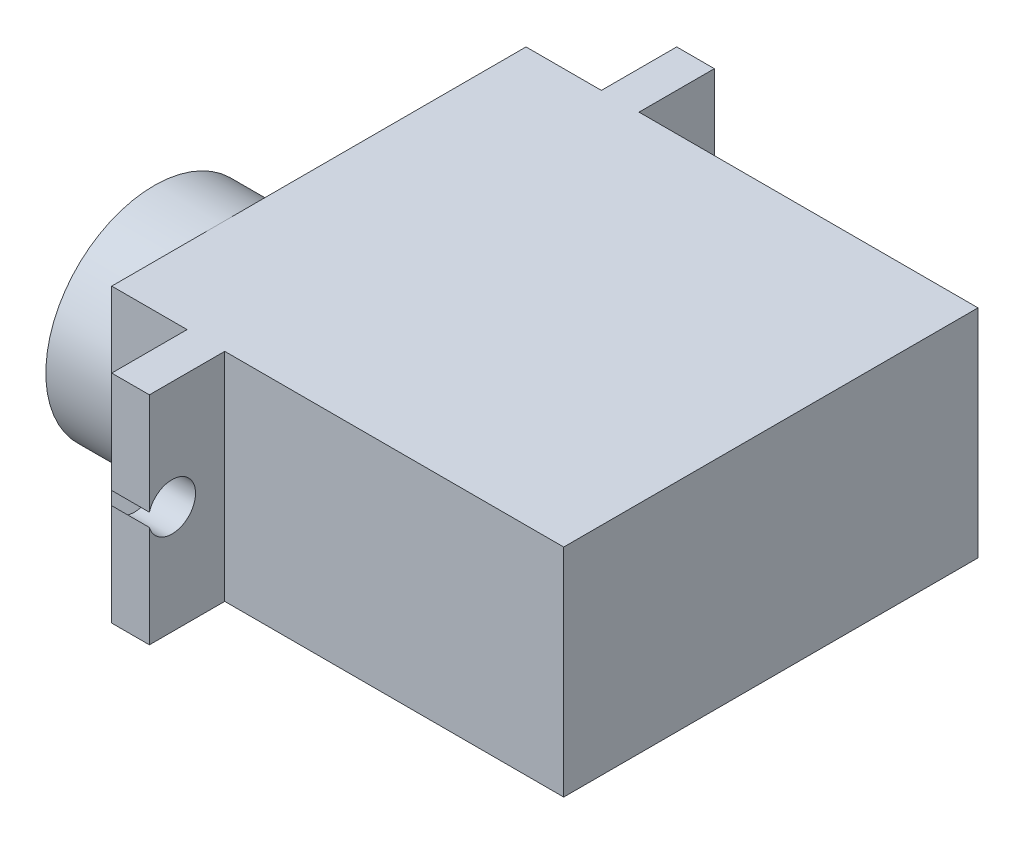
SolidWorks part; units mm, degrees
ref_plane "Front Plane" through (0, 0, 0) normal (0, 0, 1) x (1, 0, 0)
ref_plane "Top Plane" through (0, 0, 0) normal (0, 1, 0) x (1, 0, 0)
ref_plane "Right Plane" through (0, 0, 0) normal (1, 0, 0) x (0, 0, -1)
sketch "Sketch1" plane through (0, 0, 0) normal (0, 1, 0) x (1, 0, 0)
  line L0 (-20, 0) -> (-24, 0)
  line L1 (0, 0) -> (-18, 0)
  line L2 (0, 0) -> (0, 22)
  line L3 (0, 22) -> (-18, 22)
  line L4 (-24, 0) -> (-24, 22)
  line L6 (-20, 0) -> (-20, -4)
  line L7 (-20, -4) -> (-18, -4)
  line L8 (-18, 0) -> (-18, -4)
  line L10 (-20, 22) -> (-20, 26)
  line L11 (-20, 26) -> (-18, 26)
  line L12 (-18, 22) -> (-18, 26)
  line L13 (-20, 22) -> (-24, 22)
  dimension "D1" = 24
  dimension "D2" = 22
  dimension "D3" = 30
  dimension "D4" = 4
  dimension "D5" = 2
extrude "Boss-Extrude1" add sketch "Sketch1" along normal blind 11.5
sketch "Sketch2" plane through (-24, 0, 0) normal (-1, 0, 0) x (0, 0, 1)
  line L1 (-5.75, 5.75) -> (-5.75, 0) construction
  line L2 (-22, 0) -> (0, 0) construction
  line L3 (-5.75, 5.75) -> (-5.75, 11.5) construction
  line L4 (-22, 11.5) -> (0, 11.5) construction
  line L5 (0, 11.5) -> (0, 0) construction
  line L6 (-11.141, 5.75) -> (-5.75, 5.75) construction
  line L7 (-11.141, 3.75) -> (-11.141, 7.75) construction
  arc A0 (-11.141, 3.75) -> (-11.141, 7.75) centre (-5.75, 5.75) ccw
  arc A1 (-11.141, 7.75) -> (-11.141, 3.75) centre (-11.141, 5.75) ccw
  dimension "D1" = 4
extrude "Boss-Extrude2" add sketch "Sketch2" along normal blind 3.5
sketch "Sketch4" plane through (-27.5, 0, 0) normal (-1, 0, 0) x (0, 0, 1)
  circle A0 centre (-5.75, 5.75) radius 1.5
  arc A1 (-11.141, 3.75) -> (-11.141, 7.75) centre (-5.75, 5.75) ccw construction
  dimension "D1" = 3
extrude "Boss-Extrude3" add sketch "Sketch4" along normal blind 3
sketch "Sketch5" plane through (-20, 0, 0) normal (-1, 0, 0) x (0, 0, 1)
  line L2 (-26, 5.75) -> (4.05, 5.75) construction
  line L3 (-26, 11.5) -> (-26, 0) construction
  line L4 (4, 11.5) -> (4, 0) construction
  circle A0 centre (-24.8, 5.75) radius 1.25
  circle A1 centre (2.8, 5.75) radius 1.25
  dimension "D1" = 2.5
  dimension "D2" = 1.2
  dimension "D3" = 1.2
extrude "Cut-Extrude1" cut sketch "Sketch5" against normal blind 3.5
